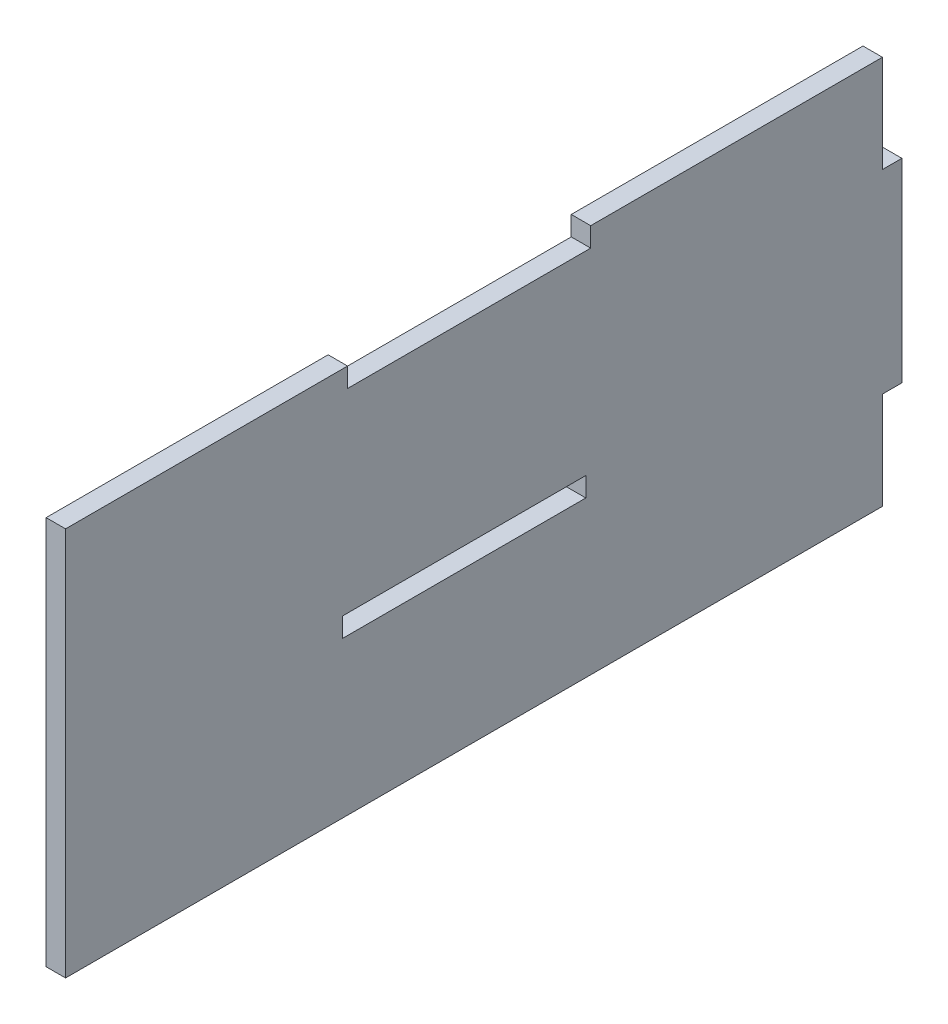
SolidWorks part; units mm, degrees
ref_plane "정면" through (0, 0, 0) normal (0, 0, 1) x (1, 0, 0)
ref_plane "윗면" through (0, 0, 0) normal (0, 1, 0) x (1, 0, 0)
ref_plane "우측면" through (0, 0, 0) normal (1, 0, 0) x (0, 0, -1)
sketch "스케치1" plane through (0, 0, 0) normal (1, 0, 0) x (0, 0, -1)
  line L1 (-87, 40) -> (87, 40)
  line L2 (-87, 40) -> (-87, -40)
  line L3 (-87, -40) -> (87, -40)
  line L4 (87, 40) -> (87, -40)
  line L5 (-87, 40) -> (87, -40) construction
  line L6 (-87, -40) -> (87, 40) construction
  point P0 (0, 0)
  dimension "D1" = 174
  dimension "D2" = 80
extrude "보스-돌출1" add sketch "스케치1" along normal blind 4
sketch "스케치3" plane through (4, 0, 0) normal (1, 0, 0) x (0, 0, -1)
  line L1 (87, 40) -> (83, 40)
  line L2 (87, 40) -> (87, 20)
  line L3 (87, 20) -> (83, 20)
  line L4 (83, 40) -> (83, 20)
  line L5 (87, -40) -> (83, -40)
  line L6 (87, -40) -> (87, -20)
  line L7 (87, -20) -> (83, -20)
  line L8 (83, -40) -> (83, -20)
  dimension "D1" = 20
  dimension "D2" = 4
  dimension "D3" = 20
  dimension "D4" = 4
extrude "컷-돌출1" cut sketch "스케치3" against normal blind 4
sketch "스케치4" plane through (4, 0, 0) normal (1, 0, 0) x (0, 0, -1)
  line L0 (83, 40) -> (-87, 40) construction
  line L1 (-27, 40) -> (23, 40)
  line L2 (-27, 40) -> (-27, 36)
  line L3 (-27, 36) -> (23, 36)
  line L4 (23, 40) -> (23, 36)
  line L5 (-87, 40) -> (-87, -40) construction
  dimension "D1" = 60
  dimension "D2" = 50
  dimension "D3" = 4
extrude "컷-돌출2" cut sketch "스케치4" against normal blind 4
sketch "스케치5" plane through (4, 0, 0) normal (1, 0, 0) x (0, 0, -1)
  line L0 (-87, -40) -> (83, -40) construction
  line L1 (-87, 40) -> (-85, 40)
  line L2 (-87, 40) -> (-87, -40)
  line L3 (-87, -40) -> (-85, -40)
  line L4 (-85, 40) -> (-85, -40)
  dimension "D1" = 2
extrude "컷-돌출3" cut sketch "스케치5" against normal blind 10
sketch "스케치6" plane through (4, 0, 0) normal (1, 0, 0) x (0, 0, -1)
  line L0 (-27, 40) -> (-85, 40) construction
  line L1 (-28, -4) -> (22, -4)
  line L2 (-28, -4) -> (-28, -8)
  line L3 (-28, -8) -> (22, -8)
  line L4 (22, -4) -> (22, -8)
  line L5 (87, -20) -> (87, 20) construction
  dimension "D1" = 50
  dimension "D2" = 4
  dimension "D3" = 44
  dimension "D4" = 65
extrude "컷-돌출4" cut sketch "스케치6" against normal blind 4
